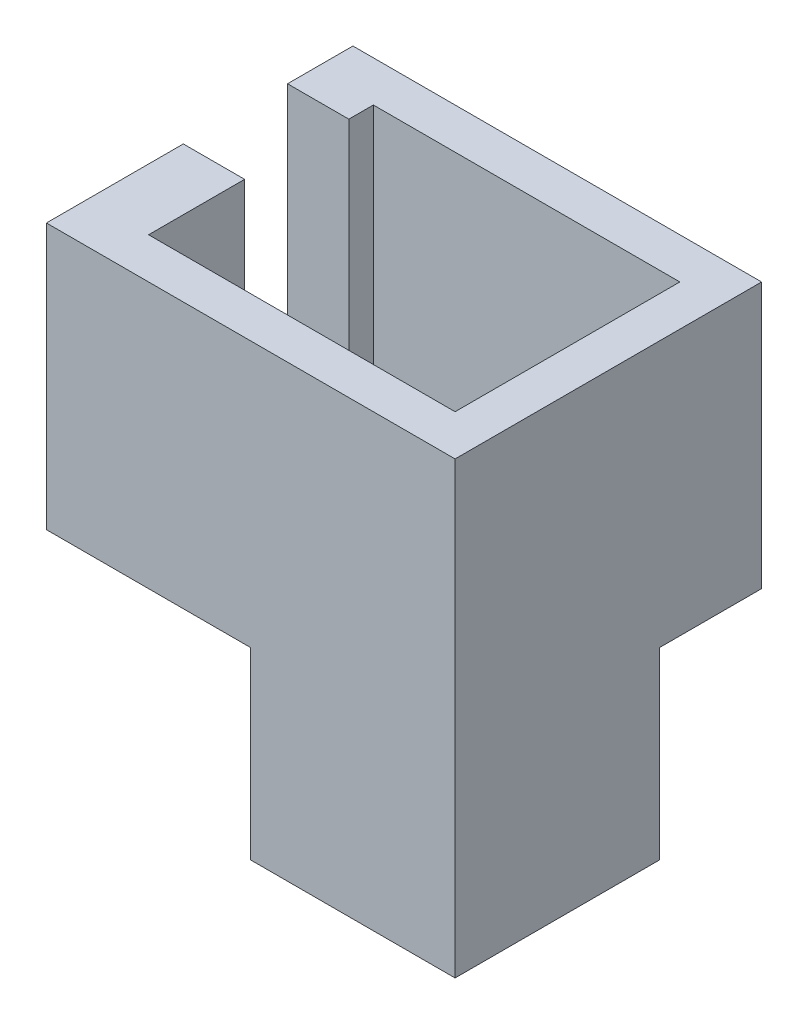
SolidWorks part; units mm, degrees
ref_plane "Front Plane" through (0, 0, 0) normal (0, 0, 1) x (1, 0, 0)
ref_plane "Top Plane" through (0, 0, 0) normal (0, 1, 0) x (1, 0, 0)
ref_plane "Right Plane" through (0, 0, 0) normal (1, 0, 0) x (0, 0, -1)
sketch "Sketch1" plane through (0, 0, 0) normal (0, 1, 0) x (1, 0, 0)
  line L3 (3, 2) -> (18, 2)
  line L8 (18, 2) -> (18, 13)
  line L11 (18, 13) -> (3, 13)
  line L13 (20, 0) -> (20, 15)
  line L15 (0, 15) -> (20, 15)
  line L22 (0, 6.7) -> (3, 6.7)
  line L23 (3, 2) -> (3, 6.7)
  line L24 (0, 0) -> (20, 0)
  line L25 (0, 0) -> (0, 6.7)
  line L29 (0, 15) -> (0, 11.8)
  line L30 (0, 11.8) -> (3, 11.8)
  line L31 (3, 11.8) -> (3, 13)
  dimension "D1" = 2
  dimension "D2" = 15
  dimension "D3" = 20
  dimension "D4" = 2
  dimension "D5" = 20
  dimension "D6" = 2
  dimension "D7" = 3.2
  dimension "D8" = 6.7
  dimension "D9" = 3
  dimension "D10" = 3
extrude "Boss-Extrude1" add sketch "Sketch1" along normal blind 12
sketch "Sketch3" plane through (0, 0, 0) normal (0, -1, 0) x (1, 0, 0)
  line L1 (20, 0) -> (0, 0)
  line L2 (20, 0) -> (20, -15)
  line L3 (20, -15) -> (0, -15)
  line L4 (0, 0) -> (0, -15)
extrude "Boss-Extrude2" add sketch "Sketch3" along normal blind 1
sketch "Sketch4" plane through (0, -1, 0) normal (0, -1, 0) x (1, 0, 0)
  line L1 (20, 0) -> (10, 0)
  line L2 (20, 0) -> (20, -10)
  line L3 (20, -10) -> (10, -10)
  line L4 (10, 0) -> (10, -10)
  line L5 (20, 0) -> (0, 0) construction
  dimension "D1" = 10
  dimension "D2" = 10
  dimension "D3" = 0
extrude "Boss-Extrude3" add sketch "Sketch4" along normal blind 9
sketch "Sketch5" plane through (18, 0, 0) normal (-1, 0, 0) x (0, 0, 1)
  line L0 (-13, 12) -> (-13, 0) construction
  line L1 (-13, 0) -> (-2, 0) construction
  circle A0 centre (-10.49, 2.51) radius 2.5
  dimension "D1" = 5
  dimension "D3" = 2.51
  dimension "D2" = 2.51
extrude "Boss-Extrude7" add sketch "Sketch5" along normal blind 0.1
